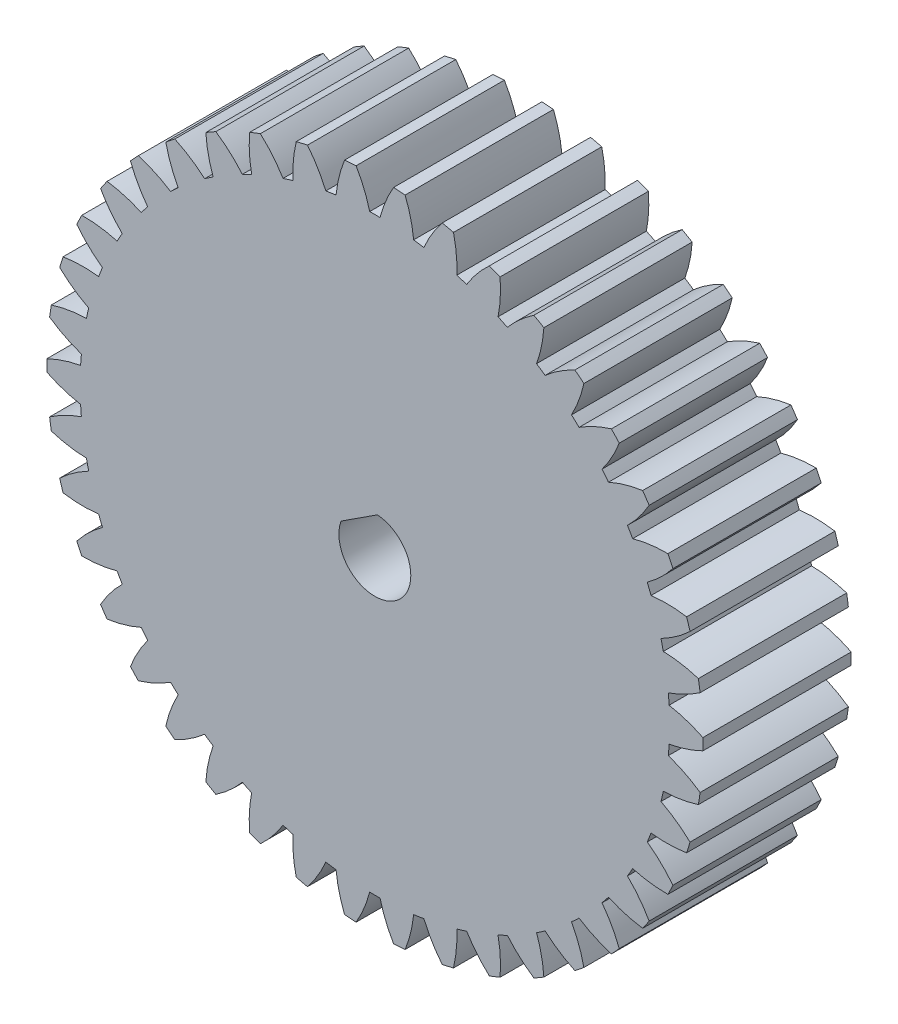
SolidWorks part; units mm, degrees
ref_plane "Front Plane" through (0, 0, 0) normal (0, 0, 1) x (1, 0, 0)
ref_plane "Top Plane" through (0, 0, 0) normal (0, 1, 0) x (1, 0, 0)
ref_plane "Right Plane" through (0, 0, 0) normal (1, 0, 0) x (0, 0, -1)
sketch "Model" plane through (0, 0, 0) normal (0, 0, 1) x (1, 0, 0)
  line L1 (0.1713, 2.4189) -> (-2.2775, 0.8329)
  arc A168 (-22.1216, -0.389) -> (-19.8414, -1.137) centre (-18.3508, 7.2567) ccw
  arc A169 (-2.2775, 0.8329) -> (0.1713, 2.4189) centre (0, 0) ccw
  arc A170 (-19.8414, -1.137) -> (-19.7893, -1.8329) centre (0, 0) ccw
  arc A171 (-19.7893, -1.8329) -> (-21.9325, -2.9124) centre (-17.0643, -9.9107) ccw
  arc A172 (-21.9325, -2.9124) -> (-21.8165, -3.6817) centre (0, 0) ccw
  arc A173 (-21.8165, -3.6817) -> (-19.4504, -4.0815) centre (-19.2274, 4.4406) ccw
  arc A174 (-19.4504, -4.0815) -> (-19.2951, -4.7619) centre (0, 0) ccw
  arc A175 (-19.2951, -4.7619) -> (-21.2535, -6.1487) centre (-15.3966, -12.3433) ccw
  arc A176 (-21.2535, -6.1487) -> (-21.0241, -6.8922) centre (0, 0) ccw
  arc A177 (-21.0241, -6.8922) -> (-18.6248, -6.9348) centre (-19.6745, 1.5253) ccw
  arc A178 (-18.6248, -6.9348) -> (-18.3698, -7.5845) centre (0, 0) ccw
  arc A179 (-18.3698, -7.5845) -> (-20.0997, -9.2477) centre (-13.385, -14.5002) ccw
  arc A180 (-20.0997, -9.2477) -> (-19.7621, -9.9487) centre (0, 0) ccw
  arc A181 (-19.7621, -9.9487) -> (-17.3832, -9.6333) centre (-19.6821, -1.4241) ccw
  arc A182 (-17.3832, -9.6333) -> (-17.0343, -10.2377) centre (0, 0) ccw
  arc A183 (-17.0343, -10.2377) -> (-18.4969, -12.1401) centre (-11.0743, -16.3331) ccw
  arc A184 (-18.4969, -12.1401) -> (-18.0586, -12.783) centre (0, 0) ccw
  arc A185 (-18.0586, -12.783) -> (-15.7533, -12.1165) centre (-19.25, -4.3416) ccw
  arc A186 (-15.7533, -12.1165) -> (-15.3182, -12.6621) centre (0, 0) ccw
  arc A187 (-15.3182, -12.6621) -> (-16.4809, -14.7613) centre (-8.5163, -17.8013) ccw
  arc A188 (-16.4809, -14.7613) -> (-15.9516, -15.3317) centre (0, 0) ccw
  arc A189 (-15.9516, -15.3317) -> (-13.7715, -14.3291) centre (-18.3879, -7.1622) ccw
  arc A190 (-13.7715, -14.3291) -> (-13.2599, -14.8038) centre (0, 0) ccw
  arc A191 (-13.2599, -14.8038) -> (-14.0967, -17.0528) centre (-5.7681, -18.8717) ccw
  arc A192 (-14.0967, -17.0528) -> (-13.4884, -17.5379) centre (0, 0) ccw
  arc A193 (-13.4884, -17.5379) -> (-11.482, -16.2216) centre (-17.1151, -9.8228) ccw
  arc A194 (-11.482, -16.2216) -> (-10.9054, -16.6147) centre (0, 0) ccw
  arc A195 (-10.9054, -16.6147) -> (-11.3977, -18.9633) centre (-2.8909, -19.5206) ccw
  arc A196 (-11.3977, -18.9633) -> (-10.7239, -19.3524) centre (0, 0) ccw
  arc A197 (-10.7239, -19.3524) -> (-8.9361, -17.7517) centre (-15.4599, -12.264) ccw
  arc A198 (-8.9361, -17.7517) -> (-8.3073, -18.0545) centre (0, 0) ccw
  arc A199 (-8.3073, -18.0545) -> (-8.4441, -20.4503) centre (0.0507, -19.7335) ccw
  arc A200 (-8.4441, -20.4503) -> (-7.7198, -20.7345) centre (0, 0) ccw
  arc A201 (-7.7198, -20.7345) -> (-6.1905, -18.8853) centre (-13.4594, -14.4312) ccw
  arc A202 (-6.1905, -18.8853) -> (-5.5236, -19.091) centre (0, 0) ccw
  arc A203 (-5.5236, -19.091) -> (-5.3018, -21.4804) centre (2.9913, -19.5055) ccw
  arc A204 (-5.3018, -21.4804) -> (-4.5432, -21.6535) centre (0, 0) ccw
  arc A205 (-4.5432, -21.6535) -> (-3.3067, -19.597) centre (-11.1582, -16.276) ccw
  arc A206 (-3.3067, -19.597) -> (-2.6166, -19.701) centre (0, 0) ccw
  arc A207 (-2.6166, -19.701) -> (-2.0411, -22.0306) centre (5.865, -18.8418) ccw
  arc A208 (-2.0411, -22.0306) -> (-1.2652, -22.0888) centre (0, 0) ccw
  arc A209 (-1.2652, -22.0888) -> (-0.3489, -19.8709) centre (-8.6078, -17.7572) ccw
  arc A210 (-0.3489, -19.8709) -> (0.3489, -19.8709) centre (0, 0) ccw
  arc A211 (0.3489, -19.8709) -> (1.2652, -22.0888) centre (8.6078, -17.7572) ccw
  arc A212 (1.2652, -22.0888) -> (2.0411, -22.0306) centre (0, 0) ccw
  arc A213 (2.0411, -22.0306) -> (2.6166, -19.701) centre (-5.865, -18.8418) ccw
  arc A214 (2.6166, -19.701) -> (3.3067, -19.597) centre (0, 0) ccw
  arc A215 (3.3067, -19.597) -> (4.5432, -21.6535) centre (11.1582, -16.276) ccw
  arc A216 (4.5432, -21.6535) -> (5.3018, -21.4804) centre (0, 0) ccw
  arc A217 (5.3018, -21.4804) -> (5.5236, -19.091) centre (-2.9913, -19.5055) ccw
  arc A218 (5.5236, -19.091) -> (6.1905, -18.8853) centre (0, 0) ccw
  arc A219 (6.1905, -18.8853) -> (7.7198, -20.7345) centre (13.4594, -14.4312) ccw
  arc A220 (7.7198, -20.7345) -> (8.4441, -20.4503) centre (0, 0) ccw
  arc A221 (8.4441, -20.4503) -> (8.3073, -18.0545) centre (-0.0507, -19.7335) ccw
  arc A222 (8.3073, -18.0545) -> (8.9361, -17.7517) centre (0, 0) ccw
  arc A223 (8.9361, -17.7517) -> (10.7239, -19.3524) centre (15.4599, -12.264) ccw
  arc A224 (10.7239, -19.3524) -> (11.3977, -18.9633) centre (0, 0) ccw
  arc A225 (11.3977, -18.9633) -> (10.9054, -16.6147) centre (2.8909, -19.5206) ccw
  arc A226 (10.9054, -16.6147) -> (11.482, -16.2216) centre (0, 0) ccw
  arc A227 (11.482, -16.2216) -> (13.4884, -17.5379) centre (17.1151, -9.8228) ccw
  arc A228 (13.4884, -17.5379) -> (14.0967, -17.0528) centre (0, 0) ccw
  arc A229 (14.0967, -17.0528) -> (13.2599, -14.8038) centre (5.7681, -18.8717) ccw
  arc A230 (13.2599, -14.8038) -> (13.7715, -14.3291) centre (0, 0) ccw
  arc A231 (13.7715, -14.3291) -> (15.9516, -15.3317) centre (18.3879, -7.1622) ccw
  arc A232 (15.9516, -15.3317) -> (16.4809, -14.7613) centre (0, 0) ccw
  arc A233 (16.4809, -14.7613) -> (15.3182, -12.6621) centre (8.5163, -17.8013) ccw
  arc A234 (15.3182, -12.6621) -> (15.7533, -12.1165) centre (0, 0) ccw
  arc A235 (15.7533, -12.1165) -> (18.0586, -12.783) centre (19.25, -4.3416) ccw
  arc A236 (18.0586, -12.783) -> (18.4969, -12.1401) centre (0, 0) ccw
  arc A237 (18.4969, -12.1401) -> (17.0343, -10.2377) centre (11.0743, -16.3331) ccw
  arc A238 (17.0343, -10.2377) -> (17.3832, -9.6333) centre (0, 0) ccw
  arc A239 (17.3832, -9.6333) -> (19.7621, -9.9487) centre (19.6821, -1.4241) ccw
  arc A240 (19.7621, -9.9487) -> (20.0997, -9.2477) centre (0, 0) ccw
  arc A241 (20.0997, -9.2477) -> (18.3698, -7.5845) centre (13.385, -14.5002) ccw
  arc A242 (18.3698, -7.5845) -> (18.6248, -6.9348) centre (0, 0) ccw
  arc A243 (18.6248, -6.9348) -> (21.0241, -6.8922) centre (19.6745, 1.5253) ccw
  arc A244 (21.0241, -6.8922) -> (21.2535, -6.1487) centre (0, 0) ccw
  arc A245 (21.2535, -6.1487) -> (19.2951, -4.7619) centre (15.3966, -12.3433) ccw
  arc A246 (19.2951, -4.7619) -> (19.4504, -4.0815) centre (0, 0) ccw
  arc A247 (19.4504, -4.0815) -> (21.8165, -3.6817) centre (19.2274, 4.4406) ccw
  arc A248 (21.8165, -3.6817) -> (21.9325, -2.9124) centre (0, 0) ccw
  arc A249 (21.9325, -2.9124) -> (19.7893, -1.8329) centre (17.0643, -9.9107) ccw
  arc A250 (19.7893, -1.8329) -> (19.8414, -1.137) centre (0, 0) ccw
  arc A251 (19.8414, -1.137) -> (22.1216, -0.389) centre (18.3508, 7.2567) ccw
  arc A252 (22.1216, -0.389) -> (22.1216, 0.389) centre (0, 0) ccw
  arc A253 (22.1216, 0.389) -> (19.8414, 1.137) centre (18.3508, -7.2567) ccw
  arc A254 (19.8414, 1.137) -> (19.7893, 1.8329) centre (0, 0) ccw
  arc A255 (19.7893, 1.8329) -> (21.9325, 2.9124) centre (17.0643, 9.9107) ccw
  arc A256 (21.9325, 2.9124) -> (21.8165, 3.6817) centre (0, 0) ccw
  arc A257 (21.8165, 3.6817) -> (19.4504, 4.0815) centre (19.2274, -4.4406) ccw
  arc A258 (19.4504, 4.0815) -> (19.2951, 4.7619) centre (0, 0) ccw
  arc A259 (19.2951, 4.7619) -> (21.2535, 6.1487) centre (15.3966, 12.3433) ccw
  arc A260 (21.2535, 6.1487) -> (21.0241, 6.8922) centre (0, 0) ccw
  arc A261 (21.0241, 6.8922) -> (18.6248, 6.9348) centre (19.6745, -1.5253) ccw
  arc A262 (18.6248, 6.9348) -> (18.3698, 7.5845) centre (0, 0) ccw
  arc A263 (18.3698, 7.5845) -> (20.0997, 9.2477) centre (13.385, 14.5002) ccw
  arc A264 (20.0997, 9.2477) -> (19.7621, 9.9487) centre (0, 0) ccw
  arc A265 (19.7621, 9.9487) -> (17.3832, 9.6333) centre (19.6821, 1.4241) ccw
  arc A266 (17.3832, 9.6333) -> (17.0343, 10.2377) centre (0, 0) ccw
  arc A267 (17.0343, 10.2377) -> (18.4969, 12.1401) centre (11.0743, 16.3331) ccw
  arc A268 (18.4969, 12.1401) -> (18.0586, 12.783) centre (0, 0) ccw
  arc A269 (18.0586, 12.783) -> (15.7533, 12.1165) centre (19.25, 4.3416) ccw
  arc A270 (15.7533, 12.1165) -> (15.3182, 12.6621) centre (0, 0) ccw
  arc A271 (15.3182, 12.6621) -> (16.4809, 14.7613) centre (8.5163, 17.8013) ccw
  arc A272 (16.4809, 14.7613) -> (15.9516, 15.3317) centre (0, 0) ccw
  arc A273 (15.9516, 15.3317) -> (13.7715, 14.3291) centre (18.3879, 7.1622) ccw
  arc A274 (13.7715, 14.3291) -> (13.2599, 14.8038) centre (0, 0) ccw
  arc A275 (13.2599, 14.8038) -> (14.0967, 17.0528) centre (5.7681, 18.8717) ccw
  arc A276 (14.0967, 17.0528) -> (13.4884, 17.5379) centre (0, 0) ccw
  arc A277 (13.4884, 17.5379) -> (11.482, 16.2216) centre (17.1151, 9.8228) ccw
  arc A278 (11.482, 16.2216) -> (10.9054, 16.6147) centre (0, 0) ccw
  arc A279 (10.9054, 16.6147) -> (11.3977, 18.9633) centre (2.8909, 19.5206) ccw
  arc A280 (11.3977, 18.9633) -> (10.7239, 19.3524) centre (0, 0) ccw
  arc A281 (10.7239, 19.3524) -> (8.9361, 17.7517) centre (15.4599, 12.264) ccw
  arc A282 (8.9361, 17.7517) -> (8.3073, 18.0545) centre (0, 0) ccw
  arc A283 (8.3073, 18.0545) -> (8.4441, 20.4503) centre (-0.0507, 19.7335) ccw
  arc A284 (8.4441, 20.4503) -> (7.7198, 20.7345) centre (0, 0) ccw
  arc A285 (7.7198, 20.7345) -> (6.1905, 18.8853) centre (13.4594, 14.4312) ccw
  arc A286 (6.1905, 18.8853) -> (5.5236, 19.091) centre (0, 0) ccw
  arc A287 (5.5236, 19.091) -> (5.3018, 21.4804) centre (-2.9913, 19.5055) ccw
  arc A288 (5.3018, 21.4804) -> (4.5432, 21.6535) centre (0, 0) ccw
  arc A289 (4.5432, 21.6535) -> (3.3067, 19.597) centre (11.1582, 16.276) ccw
  arc A290 (3.3067, 19.597) -> (2.6166, 19.701) centre (0, 0) ccw
  arc A291 (2.6166, 19.701) -> (2.0411, 22.0306) centre (-5.865, 18.8418) ccw
  arc A292 (2.0411, 22.0306) -> (1.2652, 22.0888) centre (0, 0) ccw
  arc A293 (1.2652, 22.0888) -> (0.3489, 19.8709) centre (8.6078, 17.7572) ccw
  arc A294 (0.3489, 19.8709) -> (-0.3489, 19.8709) centre (0, 0) ccw
  arc A295 (-0.3489, 19.8709) -> (-1.2652, 22.0888) centre (-8.6078, 17.7572) ccw
  arc A296 (-1.2652, 22.0888) -> (-2.0411, 22.0306) centre (0, 0) ccw
  arc A297 (-2.0411, 22.0306) -> (-2.6166, 19.701) centre (5.865, 18.8418) ccw
  arc A298 (-2.6166, 19.701) -> (-3.3067, 19.597) centre (0, 0) ccw
  arc A299 (-3.3067, 19.597) -> (-4.5432, 21.6535) centre (-11.1582, 16.276) ccw
  arc A300 (-4.5432, 21.6535) -> (-5.3018, 21.4804) centre (0, 0) ccw
  arc A301 (-5.3018, 21.4804) -> (-5.5236, 19.091) centre (2.9913, 19.5055) ccw
  arc A302 (-5.5236, 19.091) -> (-6.1905, 18.8853) centre (0, 0) ccw
  arc A303 (-6.1905, 18.8853) -> (-7.7198, 20.7345) centre (-13.4594, 14.4312) ccw
  arc A304 (-7.7198, 20.7345) -> (-8.4441, 20.4503) centre (0, 0) ccw
  arc A305 (-8.4441, 20.4503) -> (-8.3073, 18.0545) centre (0.0507, 19.7335) ccw
  arc A306 (-8.3073, 18.0545) -> (-8.9361, 17.7517) centre (0, 0) ccw
  arc A307 (-8.9361, 17.7517) -> (-10.7239, 19.3524) centre (-15.4599, 12.264) ccw
  arc A308 (-10.7239, 19.3524) -> (-11.3977, 18.9633) centre (0, 0) ccw
  arc A309 (-11.3977, 18.9633) -> (-10.9054, 16.6147) centre (-2.8909, 19.5206) ccw
  arc A310 (-10.9054, 16.6147) -> (-11.482, 16.2216) centre (0, 0) ccw
  arc A311 (-11.482, 16.2216) -> (-13.4884, 17.5379) centre (-17.1151, 9.8228) ccw
  arc A312 (-13.4884, 17.5379) -> (-14.0967, 17.0528) centre (0, 0) ccw
  arc A313 (-14.0967, 17.0528) -> (-13.2599, 14.8038) centre (-5.7681, 18.8717) ccw
  arc A314 (-13.2599, 14.8038) -> (-13.7715, 14.3291) centre (0, 0) ccw
  arc A315 (-13.7715, 14.3291) -> (-15.9516, 15.3317) centre (-18.3879, 7.1622) ccw
  arc A316 (-15.9516, 15.3317) -> (-16.4809, 14.7613) centre (0, 0) ccw
  arc A317 (-16.4809, 14.7613) -> (-15.3182, 12.6621) centre (-8.5163, 17.8013) ccw
  arc A318 (-15.3182, 12.6621) -> (-15.7533, 12.1165) centre (0, 0) ccw
  arc A319 (-15.7533, 12.1165) -> (-18.0586, 12.783) centre (-19.25, 4.3416) ccw
  arc A320 (-18.0586, 12.783) -> (-18.4969, 12.1401) centre (0, 0) ccw
  arc A321 (-18.4969, 12.1401) -> (-17.0343, 10.2377) centre (-11.0743, 16.3331) ccw
  arc A322 (-17.0343, 10.2377) -> (-17.3832, 9.6333) centre (0, 0) ccw
  arc A323 (-17.3832, 9.6333) -> (-19.7621, 9.9487) centre (-19.6821, 1.4241) ccw
  arc A324 (-19.7621, 9.9487) -> (-20.0997, 9.2477) centre (0, 0) ccw
  arc A325 (-20.0997, 9.2477) -> (-18.3698, 7.5845) centre (-13.385, 14.5002) ccw
  arc A326 (-18.3698, 7.5845) -> (-18.6248, 6.9348) centre (0, 0) ccw
  arc A327 (-18.6248, 6.9348) -> (-21.0241, 6.8922) centre (-19.6745, -1.5253) ccw
  arc A328 (-21.0241, 6.8922) -> (-21.2535, 6.1487) centre (0, 0) ccw
  arc A329 (-21.2535, 6.1487) -> (-19.2951, 4.7619) centre (-15.3966, 12.3433) ccw
  arc A330 (-19.2951, 4.7619) -> (-19.4504, 4.0815) centre (0, 0) ccw
  arc A331 (-19.4504, 4.0815) -> (-21.8165, 3.6817) centre (-19.2274, -4.4406) ccw
  arc A332 (-21.8165, 3.6817) -> (-21.9325, 2.9124) centre (0, 0) ccw
  arc A333 (-21.9325, 2.9124) -> (-19.7893, 1.8329) centre (-17.0643, 9.9107) ccw
  arc A334 (-19.7893, 1.8329) -> (-19.8414, 1.137) centre (0, 0) ccw
  arc A335 (-19.8414, 1.137) -> (-22.1216, 0.389) centre (-18.3508, -7.2567) ccw
  arc A336 (-22.1216, 0.389) -> (-22.1216, -0.389) centre (0, 0) ccw
extrude "Boss-Extrude1" add sketch "Model" along normal blind 10
